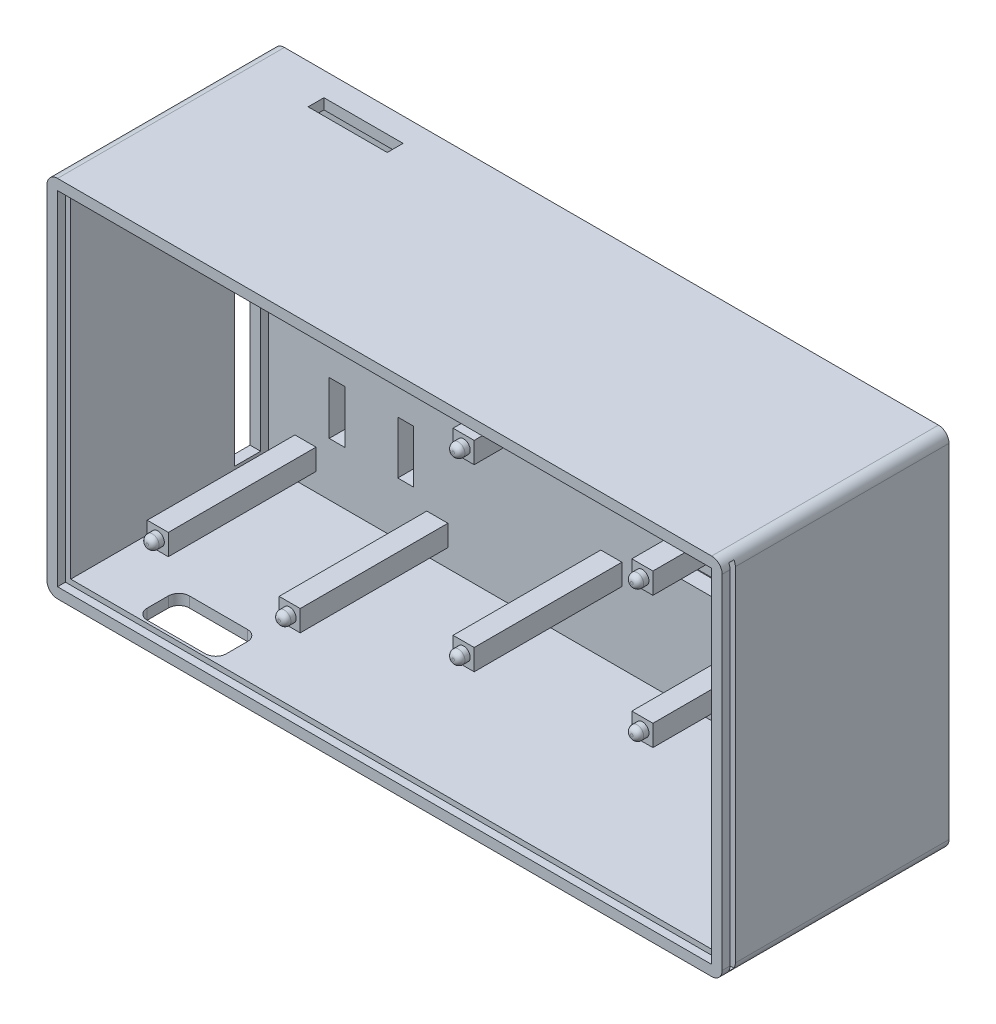
SolidWorks part; units mm, degrees
ref_plane "Alzado" through (0, 0, 0) normal (0, 0, 1) x (1, 0, 0)
ref_plane "Planta" through (0, 0, 0) normal (0, 1, 0) x (1, 0, 0)
ref_plane "Vista lateral" through (0, 0, 0) normal (1, 0, 0) x (0, 0, -1)
sketch "Croquis1" plane through (0, 0, 0) normal (0, 0, 1) x (1, 0, 0)
  line L1 (-57.5, 29.5) -> (57.5, 29.5) construction
  line L2 (-57.5, 29.5) -> (-57.5, -29.5) construction
  line L3 (-57.5, -29.5) -> (57.5, -29.5) construction
  line L4 (57.5, 29.5) -> (57.5, -29.5) construction
  line L5 (62, -32.5) -> (-62, -32.5) construction
  line L6 (62, -32.5) -> (62, 32.5) construction
  line L7 (62, 32.5) -> (-62, 32.5) construction
  line L8 (-62, -32.5) -> (-62, 32.5) construction
  line L9 (62, -32.5) -> (-62, 32.5) construction
  line L10 (62, 32.5) -> (-62, -32.5) construction
  line L11 (62, -34.5) -> (-62, -34.5)
  line L12 (64, -32.5) -> (64, 32.5)
  line L13 (62, 34.5) -> (-62, 34.5)
  line L14 (-64, -32.5) -> (-64, 32.5)
  line L15 (64, -34.5) -> (-64, 34.5) construction
  line L16 (64, 34.5) -> (-64, -34.5) construction
  arc A0 (-62, -34.5) -> (-64, -32.5) centre (-62, -32.5) cw
  arc A1 (64, -32.5) -> (62, -34.5) centre (62, -32.5) cw
  arc A2 (64, 32.5) -> (62, 34.5) centre (62, 32.5) ccw
  arc A3 (-62, 34.5) -> (-64, 32.5) centre (-62, 32.5) ccw
  point P4 (0, 0)
  point P13 (0, 0)
  dimension "D9" = 2
  dimension "D1" = 115
  dimension "D2" = 57.5
  dimension "D3" = 59
  dimension "D4" = 29.5
  dimension "D5" = 62
  dimension "D6" = 32.5
  dimension "D7" = 2
  dimension "D8" = 2
extrude "Saliente-Extruir1" add sketch "Croquis1" along normal blind 3
sketch "Croquis2" plane through (0, 0, 0) normal (0, 0, 1) x (1, 0, 0)
  line L0 (-64, 32.5) -> (-64, -32.5) construction
  line L1 (62, -34.5216) -> (-62, -34.5216)
  line L2 (64, -32.5216) -> (64, 32.5216)
  line L3 (62, 34.5216) -> (-62, 34.5216)
  line L4 (-64, -32.5216) -> (-64, 32.5216)
  line L5 (64, -34.5216) -> (-64, 34.5216) construction
  line L6 (64, 34.5216) -> (-64, -34.5216) construction
  line L7 (62, -32.5216) -> (-62, -32.5216)
  line L8 (62, -32.5216) -> (62, 32.5216)
  line L9 (62, 32.5216) -> (-62, 32.5216)
  line L10 (-62, -32.5216) -> (-62, 32.5216)
  line L11 (62, -32.5216) -> (-62, 32.5216) construction
  line L12 (62, 32.5216) -> (-62, -32.5216) construction
  arc A0 (-62, -34.5216) -> (-64, -32.5216) centre (-62, -32.5216) cw
  arc A1 (64, -32.5216) -> (62, -34.5216) centre (62, -32.5216) cw
  arc A2 (64, 32.5216) -> (62, 34.5216) centre (62, 32.5216) ccw
  arc A3 (-62, 34.5216) -> (-64, 32.5216) centre (-62, 32.5216) ccw
  point P0 (0, 0)
  point P7 (0, 0)
  dimension "D3" = 2
  dimension "D1" = 2
  dimension "D2" = 2
extrude "Saliente-Extruir2" add sketch "Croquis2" along normal blind 43
sketch "Croquis3" plane through (0, 0, 0) normal (1, 0, 0) x (0, 0, -1)
  line L1 (-41.5, 33.5216) -> (-40.5, 33.5216)
  line L2 (-41.5, 33.5216) -> (-41.5, -33.5216)
  line L3 (-41.5, -33.5216) -> (-40.5, -33.5216)
  line L4 (-40.5, 33.5216) -> (-40.5, -33.5216)
  line L6 (-43, -32.5216) -> (-43, 32.5216) construction
  line L7 (-43, -34.5216) -> (0, -34.5216) construction
  line L8 (-43, 34.5216) -> (0, 34.5216) construction
  dimension "D1" = 1
  dimension "D2" = 1
  dimension "D3" = 1
  dimension "D4" = 1.5
extrude "Cortar-Extruir1" cut sketch "Croquis3" along normal up to next and the other way blind 63
sketch "Croquis4" plane through (0, 0, 0) normal (0, 0, 1) x (1, 0, 0)
  line L0 (-55, 24.903) -> (-55, -27.097) construction
  line L1 (-55, -27.097) -> (-30, -27.097) construction
  line L2 (-30, -27.097) -> (-30, 24.903) construction
  line L3 (-30, 24.903) -> (-55, 24.903) construction
  line L4 (-30, -1.097) -> (-55, -1.097) construction
  line L5 (2.9833, 17) -> (2.9833, -17) construction
  line L6 (-27, -29.597) -> (-58, -29.597) construction
  line L7 (-27, -29.597) -> (-27, 27.403) construction
  line L8 (-27, 27.403) -> (-58, 27.403) construction
  line L9 (-58, -29.597) -> (-58, 27.403) construction
  line L10 (-27, -29.597) -> (-58, 27.403) construction
  line L11 (-27, 27.403) -> (-58, -29.597) construction
  line L12 (-2, -24.5) -> (58, -24.5) construction
  line L13 (-2, -24.5) -> (-2, 24.5) construction
  line L14 (-2, 24.5) -> (58, 24.5) construction
  line L15 (58, -24.5) -> (58, 24.5) construction
  line L16 (-2, -24.5) -> (58, 24.5) construction
  line L17 (-2, 24.5) -> (58, -24.5) construction
  line L18 (36.871, 12.5) -> (36.871, -12.5) construction
  line L20 (-62, 32.5216) -> (-62, -32.5216) construction
  line L24 (-57, 22.903) -> (-53, 22.903)
  line L25 (-57, 22.903) -> (-57, 26.903)
  line L26 (-57, 26.903) -> (-53, 26.903)
  line L27 (-53, 22.903) -> (-53, 26.903)
  line L28 (-57, 22.903) -> (-53, 26.903) construction
  line L29 (-57, 26.903) -> (-53, 22.903) construction
  line L30 (-32, 22.903) -> (-28, 22.903)
  line L31 (-32, 22.903) -> (-32, 26.903)
  line L32 (-32, 26.903) -> (-28, 26.903)
  line L33 (-28, 22.903) -> (-28, 26.903)
  line L34 (-32, 22.903) -> (-28, 26.903) construction
  line L35 (-32, 26.903) -> (-28, 22.903) construction
  line L36 (-57, -29.097) -> (-53, -29.097)
  line L37 (-57, -29.097) -> (-57, -25.097)
  line L38 (-57, -25.097) -> (-53, -25.097)
  line L39 (-53, -29.097) -> (-53, -25.097)
  line L40 (-57, -29.097) -> (-53, -25.097) construction
  line L41 (-57, -25.097) -> (-53, -29.097) construction
  line L42 (-28, -29.097) -> (-32, -29.097)
  line L43 (-28, -29.097) -> (-28, -25.097)
  line L44 (-28, -25.097) -> (-32, -25.097)
  line L45 (-32, -29.097) -> (-32, -25.097)
  line L46 (-28, -29.097) -> (-32, -25.097) construction
  line L47 (-28, -25.097) -> (-32, -29.097) construction
  line L48 (4.9833, 15) -> (0.9833, 15)
  line L49 (4.9833, 15) -> (4.9833, 19)
  line L50 (4.9833, 19) -> (0.9833, 19)
  line L51 (0.9833, 15) -> (0.9833, 19)
  line L52 (4.9833, 15) -> (0.9833, 19) construction
  line L53 (4.9833, 19) -> (0.9833, 15) construction
  line L54 (0.9833, -19) -> (4.9833, -19)
  line L55 (0.9833, -19) -> (0.9833, -15)
  line L56 (0.9833, -15) -> (4.9833, -15)
  line L57 (4.9833, -19) -> (4.9833, -15)
  line L58 (0.9833, -19) -> (4.9833, -15) construction
  line L59 (0.9833, -15) -> (4.9833, -19) construction
  line L60 (34.871, -10.5) -> (38.871, -10.5)
  line L61 (34.871, -10.5) -> (34.871, -14.5)
  line L62 (34.871, -14.5) -> (38.871, -14.5)
  line L63 (38.871, -10.5) -> (38.871, -14.5)
  line L64 (34.871, -10.5) -> (38.871, -14.5) construction
  line L65 (34.871, -14.5) -> (38.871, -10.5) construction
  line L66 (38.871, 10.5) -> (34.871, 10.5)
  line L67 (38.871, 10.5) -> (38.871, 14.5)
  line L68 (38.871, 14.5) -> (34.871, 14.5)
  line L69 (34.871, 10.5) -> (34.871, 14.5)
  line L70 (38.871, 10.5) -> (34.871, 14.5) construction
  line L71 (38.871, 14.5) -> (34.871, 10.5) construction
  circle A0 centre (-55, 24.903) radius 1.25
  circle A1 centre (-30, 24.903) radius 1.25
  circle A2 centre (-55, -27.097) radius 1.25
  circle A3 centre (-30, -27.097) radius 1.25
  circle A4 centre (2.9833, 17) radius 1.25
  circle A5 centre (2.9833, -17) radius 1.25
  circle A6 centre (36.871, 12.5) radius 1.25
  circle A7 centre (36.871, -12.5) radius 1.25
  point P11 (-42.5, -1.097)
  point P16 (28, 0)
  dimension "D2" = 2.5
  dimension "D8" = 2.5
  dimension "D9" = 2.5
  dimension "D11" = 25
  dimension "D17" = 4
  dimension "D1" = 25
  dimension "D3" = 52
  dimension "D4" = 31
  dimension "D5" = 57
  dimension "D6" = 49
  dimension "D7" = 60
  dimension "D10" = 34
  dimension "D12" = 12.5
  dimension "D13" = 17
  dimension "D14" = 25
  dimension "D15" = 4
  dimension "D16" = 4
extrude "Saliente-Extruir3" add sketch "Croquis4" along normal blind 31
sketch "Croquis6" plane through (0, 0, 0) normal (0, 0, 1) x (1, 0, 0)
  circle A0 centre (-55, 24.903) radius 1.25
  circle A1 centre (-30, 24.903) radius 1.25
  circle A2 centre (-30, -27.097) radius 1.25
  circle A3 centre (-55, -27.097) radius 1.25
  circle A4 centre (2.9833, -17) radius 1.25
  circle A5 centre (36.871, -12.5) radius 1.25
  circle A6 centre (36.871, 12.5) radius 1.25
  circle A7 centre (2.9833, 17) radius 1.25
extrude "Saliente-Extruir4" add sketch "Croquis6" along normal blind 33
fillet "Redondeo3" radius 1 8 edges at (-53.75, -27.097, 33) (-28.75, -27.097, 33) (38.121, 12.5, 33) (38.121, -12.5, 33) (4.2333, -17, 33) (4.2333, 17, 33) (-53.75, 24.903, 33) (-28.75, 24.903, 33)
sketch "Croquis9" plane through (0, -34.5216, 0) normal (0, -1, 0) x (1, 0, 0)
  line L0 (-62, 0) -> (62, 0) construction
  line L1 (-48, 40) -> (-37, 40)
  line L2 (-50, 38) -> (-50, 34)
  line L3 (-48, 32) -> (-37, 32)
  line L4 (-35, 38) -> (-35, 34)
  line L8 (-42.5, 40) -> (-42.5, 32) construction
  line L9 (-64, 43) -> (-64, 0) construction
  arc A0 (-35, 38) -> (-37, 40) centre (-37, 38) ccw
  arc A1 (-35, 34) -> (-37, 32) centre (-37, 34) cw
  arc A2 (-48, 32) -> (-50, 34) centre (-48, 34) cw
  arc A3 (-48, 40) -> (-50, 38) centre (-48, 38) ccw
  point P12 (-35, 40)
  point P17 (-50, 32)
  point P20 (-50, 40)
  dimension "D5" = 2
  dimension "D1" = 8
  dimension "D2" = 15
  dimension "D3" = 32
  dimension "D4" = 21.5
extrude "Cortar-Extruir2" cut sketch "Croquis9" against normal up to next
sketch "Croquis10" plane through (-64, 0, 0) normal (-1, 0, 0) x (0, 0, 1)
  line L0 (0, 32.5216) -> (0, -32.5216) construction
  line L1 (4.5, 29.5216) -> (9.5, 29.5216)
  line L2 (4.5, 29.5216) -> (4.5, -29.5216)
  line L3 (4.5, -29.5216) -> (9.5, -29.5216)
  line L4 (9.5, 29.5216) -> (9.5, -29.5216)
  line L5 (43, 34.5216) -> (0, 34.5216) construction
  line L6 (43, -34.5216) -> (0, -34.5216) construction
  dimension "D1" = 4.5
  dimension "D2" = 5
  dimension "D3" = 5
  dimension "D4" = 5
extrude "Cortar-Extruir3" cut sketch "Croquis10" against normal up to next
sketch "Croquis11" plane through (0, 0, 0) normal (0, 0, 1) x (1, 0, 0)
  line L0 (-53, 22.903) -> (-53, 26.903) construction
  line L1 (-50.5, 20.2231) -> (-47.5, 20.2231)
  line L2 (-50.5, 20.2231) -> (-50.5, 10.2231)
  line L3 (-50.5, 10.2231) -> (-47.5, 10.2231)
  line L4 (-47.5, 20.2231) -> (-47.5, 10.2231)
  line L5 (-37.5, 20.2231) -> (-34.5, 20.2231)
  line L6 (-37.5, 20.2231) -> (-37.5, 10.2231)
  line L7 (-37.5, 10.2231) -> (-34.5, 10.2231)
  line L8 (-34.5, 20.2231) -> (-34.5, 10.2231)
  line L9 (-53, 24.903) -> (-32, 24.903) construction
  line L10 (-32, 26.903) -> (-32, 22.903) construction
  line L11 (-42.5, 24.903) -> (-42.5, 7.5727) construction
  line L12 (-55, 22.903) -> (-55, -25.097) construction
  line L13 (-57, 22.903) -> (-53, 22.903) construction
  line L14 (-53, -25.097) -> (-57, -25.097) construction
  line L15 (-55, -1.097) -> (-30.0495, -1.097) construction
  line L16 (-47.5, -22.4172) -> (-47.5, -12.4172)
  line L17 (-50.5, -12.4172) -> (-47.5, -12.4172)
  line L18 (-50.5, -22.4172) -> (-50.5, -12.4172)
  line L19 (-50.5, -22.4172) -> (-47.5, -22.4172)
  line L20 (-37.5, -22.4172) -> (-34.5, -22.4172)
  line L21 (-34.5, -22.4172) -> (-34.5, -12.4172)
  line L22 (-37.5, -12.4172) -> (-34.5, -12.4172)
  line L23 (-37.5, -22.4172) -> (-37.5, -12.4172)
  line L24 (36.871, 10.5) -> (36.871, -10.5) construction
  line L25 (12.8638, 12) -> (27.0215, 12)
  line L26 (12.8638, 12) -> (12.8638, 9)
  line L27 (12.8638, 9) -> (27.0215, 9)
  line L28 (27.0215, 12) -> (27.0215, 9)
  line L29 (12.8638, -9) -> (27.0215, -9)
  line L30 (12.8638, -9) -> (12.8638, -12.1461)
  line L31 (12.8638, -12.1461) -> (27.0215, -12.1461)
  line L32 (27.0215, -9) -> (27.0215, -12.1461)
  line L33 (34.871, 10.5) -> (38.871, 10.5) construction
  line L34 (38.871, -10.5) -> (34.871, -10.5) construction
  line L35 (36.871, 0) -> (0, 0) construction
  line L36 (-64, 32.5216) -> (-64, -32.5216) construction
  dimension "D1" = 10
  dimension "D2" = 3
  dimension "D3" = 3
  dimension "3" = 3
  dimension "D4" = 10
  dimension "D5" = 5
  dimension "D6" = 3.1461
  dimension "D7" = 18
  dimension "D8" = 9
extrude "Cortar-Extruir4" cut sketch "Croquis11" along normal up to next
sketch "Croquis13" plane through (0, 34.5216, 0) normal (0, 1, 0) x (1, 0, 0)
  line L0 (-42.5, -3.8734) -> (-42.5, -17.9052) construction
  line L1 (-50, -4.5) -> (-35, -4.5)
  line L2 (-50, -4.5) -> (-50, -7.5)
  line L3 (-50, -7.5) -> (-35, -7.5)
  line L4 (-35, -4.5) -> (-35, -7.5)
  line L5 (-64, -43) -> (-64, 0) construction
  line L6 (62, 0) -> (-62, 0) construction
  dimension "D1" = 3
  dimension "D2" = 15
  dimension "D3" = 21.5
  dimension "D4" = 7.5
  dimension "D5" = 4.5
extrude "Cortar-Extruir5" cut sketch "Croquis13" against normal up to next
